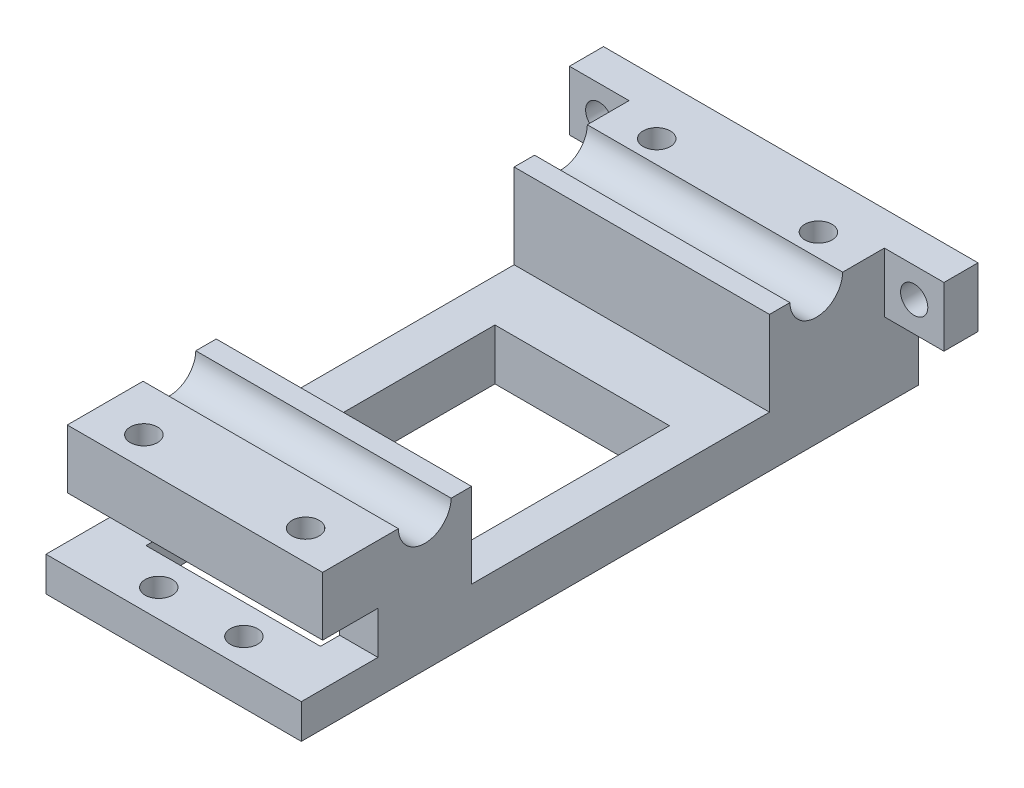
SolidWorks part; units mm, degrees
ref_plane "Front Plane" through (0, 0, 0) normal (0, 0, 1) x (1, 0, 0)
ref_plane "Top Plane" through (0, 0, 0) normal (0, 1, 0) x (1, 0, 0)
ref_plane "Right Plane" through (0, 0, 0) normal (1, 0, 0) x (0, 0, -1)
sketch "Sketch3" plane through (0, 0, 0) normal (0, 1, 0) x (1, 0, 0)
  line L1 (-15, 36.25) -> (15, 36.25)
  line L2 (-15, 36.25) -> (-15, -36.25)
  line L3 (-15, -36.25) -> (15, -36.25)
  line L4 (15, 36.25) -> (15, -36.25)
  line L5 (-15, 36.25) -> (15, -36.25) construction
  line L6 (-15, -36.25) -> (15, 36.25) construction
  point P0 (0, 0)
  dimension "D1" = 72.5
  dimension "D2" = 30
extrude "Boss-Extrude2" add sketch "Sketch3" along normal blind 15.95
sketch "Sketch7" plane through (0, 0, 0) normal (0, -1, 0) x (1, 0, 0)
  line L0 (-15, -36.25) -> (-15, 36.25) construction
  line L1 (10.5, -11.5) -> (-10, -11.5)
  line L2 (10.5, -11.5) -> (10.5, 29.5)
  line L3 (10.5, 29.5) -> (-10, 29.5)
  line L4 (-10, -11.5) -> (-10, 29.5)
  line L5 (10.5, -11.5) -> (-10, 29.5) construction
  line L6 (10.5, 29.5) -> (-10, -11.5) construction
  line L7 (-15, 36.25) -> (15, 36.25) construction
  point P0 (0.25, 9)
  dimension "D1" = 5
  dimension "D2" = 41
  dimension "D3" = 20.5
  dimension "D4" = 6.75
extrude "Cut-Extrude5" cut sketch "Sketch7" against normal blind 8
sketch "Sketch8" plane through (0, 15.95, 0) normal (0, 1, 0) x (1, 0, 0)
  line L0 (15, -36.25) -> (15, 36.25) construction
  line L1 (-15, 18.75) -> (15, 18.75)
  line L2 (-15, 18.75) -> (-15, -16.25)
  line L3 (-15, -16.25) -> (15, -16.25)
  line L4 (15, 18.75) -> (15, -16.25)
  line L5 (-15, 18.75) -> (15, -16.25) construction
  line L6 (-15, -16.25) -> (15, 18.75) construction
  line L7 (-15, -36.25) -> (15, -36.25) construction
  point P0 (0, 1.25)
  dimension "D1" = 35
  dimension "D2" = 20
extrude "Cut-Extrude6" cut sketch "Sketch8" against normal blind 9.95
sketch "Sketch9" plane through (15, 0, 0) normal (1, 0, 0) x (0, 0, -1)
  line L0 (-36.25, 15.95) -> (-33.75, 15.95)
  line L1 (-36.25, 15.95) -> (-16.25, 15.95) construction
  line L2 (-33.75, 15.95) -> (-33.75, 9.05)
  line L3 (-33.75, 9.05) -> (-27.25, 9.05)
  line L4 (-27.25, 9.05) -> (-27.25, 4.05)
  line L5 (-27.25, 4.05) -> (-36.25, 4.05)
  line L6 (-36.25, 15.95) -> (-36.25, 0) construction
  line L7 (-36.25, 4.05) -> (-36.25, 15.95)
  line L9 (-36.25, 0) -> (36.25, 0) construction
  dimension "D1" = 2.5
  dimension "D2" = 4.05
  dimension "D3" = 5
  dimension "D4" = 9
extrude "Cut-Extrude7" cut sketch "Sketch9" against normal through all
sketch "Sketch10" plane through (15, 0, 0) normal (1, 0, 0) x (0, 0, -1)
  line L0 (18.75, 15.95) -> (36.25, 15.95) construction
  line L1 (36.25, 15.95) -> (36.25, 0) construction
  circle A0 centre (24.25, 16) radius 3.1
  circle A1 centre (-21.75, 16) radius 3.1
  dimension "D1" = 6.2
  dimension "D2" = 6.2
  dimension "D4" = 12
  dimension "D5" = 46
  dimension "D3" = 0.05
extrude "Cut-Extrude8" cut sketch "Sketch10" against normal through all
sketch "Sketch11" plane through (0, 15.95, 0) normal (0, 1, 0) x (1, 0, 0)
  line L0 (15, -33.75) -> (15, -24.8496) construction
  line L1 (-15, -24.8496) -> (-15, -33.75) construction
  line L2 (-15, -33.75) -> (15, -33.75) construction
  line L3 (15, 36.25) -> (-15, 36.25) construction
  circle A0 centre (-9.5, -30.25) radius 1.6
  circle A1 centre (9.5, -30.25) radius 1.6
  circle A2 centre (-9.5, 30) radius 1.6
  circle A3 centre (9.5, 30) radius 1.6
  dimension "D1" = 3.2
  dimension "D2" = 3.2
  dimension "D3" = 5.5
  dimension "D4" = 5.5
  dimension "D5" = 3.5
  dimension "D6" = 3.2
  dimension "D7" = 3.2
  dimension "D8" = 6.25
extrude "Cut-Extrude9" cut sketch "Sketch11" against normal up to next
sketch "Sketch12" plane through (0, 4.05, 0) normal (0, 1, 0) x (1, 0, 0)
  line L1 (-10, -29.5) -> (10.5, -29.5) construction
  line L2 (-10, 11.5) -> (10.5, 11.5) construction
  circle A0 centre (-5, -33) radius 1.6
  circle A1 centre (5, -33) radius 1.6
  circle A2 centre (-5, 15) radius 1.6
  circle A3 centre (5, 15) radius 1.6
  dimension "D1" = 3.2
  dimension "D2" = 3.2
  dimension "D5" = 5
  dimension "D6" = 3.2
  dimension "D7" = 3.2
  dimension "D3" = 3.5
  dimension "D4" = 3.5
  dimension "D8" = 10
extrude "Cut-Extrude10" cut sketch "Sketch12" against normal up to next
sketch "Sketch13" plane through (0, 0, -36.25) normal (0, 0, -1) x (-1, 0, 0)
  line L1 (15, 15.95) -> (22, 15.95)
  line L2 (15, 15.95) -> (15, 8.95)
  line L3 (15, 8.95) -> (22, 8.95)
  line L4 (22, 15.95) -> (22, 8.95)
  line L5 (-15, 15.95) -> (-22, 15.95)
  line L6 (-15, 15.95) -> (-15, 8.95)
  line L7 (-15, 8.95) -> (-22, 8.95)
  line L8 (-22, 15.95) -> (-22, 8.95)
  circle A0 centre (18.5, 12.45) radius 1.6
  circle A1 centre (-18.5, 12.45) radius 1.6
  dimension "D3" = 3.2
  dimension "D4" = 3.5
  dimension "D5" = 3.5
  dimension "D8" = 3.2
  dimension "D9" = 3.5
  dimension "D10" = 3.5
  dimension "D1" = 7
  dimension "D2" = 7
  dimension "D6" = 7
  dimension "D7" = 7
extrude "Boss-Extrude3" add sketch "Sketch13" against normal blind 4
